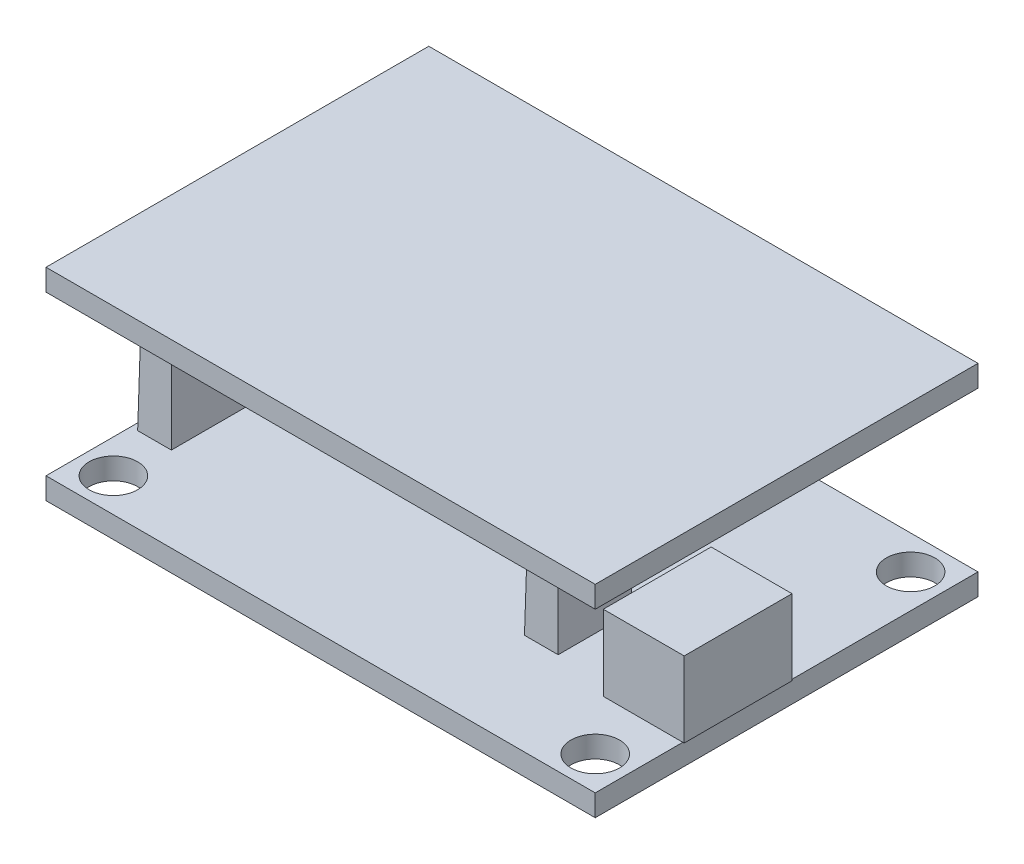
SolidWorks part; units mm, degrees
ref_plane "Plan de face" through (0, 0, 0) normal (0, 0, 1) x (1, 0, 0)
ref_plane "Plan de dessus" through (0, 0, 0) normal (0, 1, 0) x (1, 0, 0)
ref_plane "Plan de droite" through (0, 0, 0) normal (1, 0, 0) x (0, 0, -1)
sketch "Esquisse1" plane through (0, 0, 0) normal (0, 1, 0) x (1, 0, 0)
  line L1 (0, 0) -> (40.75, 0)
  line L2 (0, 0) -> (0, 28.4)
  line L3 (0, 28.4) -> (40.75, 28.4)
  line L4 (40.75, 0) -> (40.75, 28.4)
  dimension "D1" = 40.75
  dimension "D2" = 28.4
extrude "Boss.-Extru.1" add sketch "Esquisse1" along normal blind 1.6
sketch "Esquisse2" plane through (0, 1.6, 0) normal (0, 1, 0) x (1, 0, 0)
  line L0 (40.75, 28.4) -> (0, 28.4) construction
  line L1 (2.5, 25.9) -> (38.25, 25.9) construction
  line L2 (2.5, 25.9) -> (2.5, 2.5) construction
  line L3 (2.5, 2.5) -> (38.25, 2.5) construction
  line L4 (38.25, 25.9) -> (38.25, 2.5) construction
  line L5 (40.75, 0) -> (40.75, 28.4) construction
  line L6 (0, 28.4) -> (0, 0) construction
  line L7 (0, 0) -> (40.75, 0) construction
  circle A0 centre (2.5, 25.9) radius 1.8
  circle A1 centre (38.25, 25.9) radius 1.8
  circle A2 centre (38.25, 2.5) radius 1.8
  circle A3 centre (2.5, 2.5) radius 1.8
  dimension "D1" = 3.6
  dimension "D2" = 2.5
  dimension "D3" = 2.5
  dimension "D4" = 2.5
  dimension "D5" = 2.5
extrude "Enlèv. mat.-Extru.1" cut sketch "Esquisse2" against normal through all
sketch "Esquisse3" plane through (0, 1.6, 0) normal (0, 1, 0) x (1, 0, 0)
  line L0 (0, 0) -> (40.75, 0) construction
  line L1 (34.85, 14.5) -> (40.85, 14.5)
  line L2 (34.85, 14.5) -> (34.85, 6.5)
  line L3 (34.85, 6.5) -> (40.85, 6.5)
  line L4 (40.85, 14.5) -> (40.85, 6.5)
  line L6 (40.75, 0) -> (40.75, 28.4) construction
  dimension "D1" = 8
  dimension "D2" = 14.5
  dimension "D3" = 6
  dimension "D4" = 0.1
extrude "Boss.-Extru.2" add sketch "Esquisse3" along normal blind 5.6
sketch "Esquisse4" plane through (0, 1.6, 0) normal (0, -1, 0) x (1, 0, 0)
  line L0 (0, -28.4) -> (0, 0) construction
  line L1 (0.5, -6.3) -> (3, -6.3)
  line L2 (0.5, -6.3) -> (0.5, -21.5)
  line L3 (0.5, -21.5) -> (3, -21.5)
  line L4 (3, -6.3) -> (3, -21.5)
  line L5 (28, -7.5) -> (30.5, -7.5)
  line L6 (28, -7.5) -> (28, -13)
  line L7 (28, -13) -> (30.5, -13)
  line L8 (30.5, -7.5) -> (30.5, -13)
  line L9 (0, 0) -> (40.75, 0) construction
  line L10 (40.75, 0) -> (40.75, -28.4) construction
  dimension "D1" = 2.5
  dimension "D2" = 3
  dimension "D3" = 15.2
  dimension "D4" = 21.5
  dimension "D5" = 5.5
  dimension "D6" = 13
  dimension "D7" = 12.75
extrude "Boss.-Extru.3" add sketch "Esquisse4" against normal blind 8.7 draft 1
ref_plane "Plan1" through (0, 15, 0) normal (0, -1, 0) x (1, 0, 0)
sketch "Esquisse5" plane through (0, 15, 0) normal (0, -1, 0) x (1, 0, 0)
  line L1 (40.75, 0) -> (0, 0)
  line L2 (40.75, 0) -> (40.75, -28.4)
  line L3 (40.75, -28.4) -> (0, -28.4)
  line L4 (0, 0) -> (0, -28.4)
extrude "Boss.-Extru.4" add sketch "Esquisse5" along normal blind 1.6 separate body
ref_plane "Plan2" through (20.375, 0, 0) normal (-1, 0, 0) x (0, 0, 1)
ref_plane "Plan3" through (0, 0, -14.2) normal (0, 0, -1) x (-1, 0, 0)
